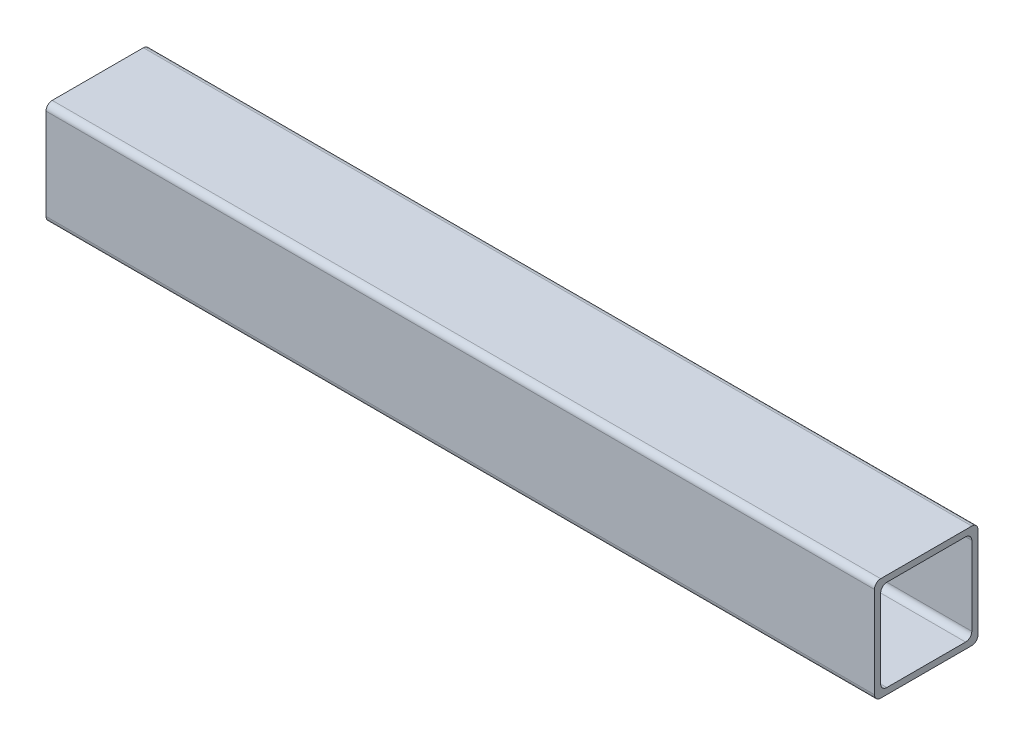
SolidWorks part; units mm, degrees
ref_plane "Front Plane" through (0, 0, 0) normal (0, 0, 1) x (1, 0, 0)
ref_plane "Top Plane" through (0, 0, 0) normal (0, 1, 0) x (1, 0, 0)
ref_plane "Right Plane" through (0, 0, 0) normal (1, 0, 0) x (0, 0, -1)
sketch "Sketch1" plane through (0, 0, 0) normal (1, 0, 0) x (0, 0, -1)
  line L1 (1.5, 0) -> (23.5, 0)
  line L2 (0, 1.5) -> (0, 23.5)
  line L3 (1.5, 25) -> (23.5, 25)
  line L4 (25, 1.5) -> (25, 23.5)
  line L5 (3, 23.5) -> (22, 23.5)
  line L6 (1.5, 22) -> (1.5, 3)
  line L7 (3, 1.5) -> (22, 1.5)
  line L8 (23.5, 22) -> (23.5, 3)
  arc A0 (23.5, 25) -> (25, 23.5) centre (23.5, 23.5) cw
  arc A1 (22, 23.5) -> (23.5, 22) centre (22, 22) cw
  arc A2 (23.5, 0) -> (25, 1.5) centre (23.5, 1.5) ccw
  arc A3 (22, 1.5) -> (23.5, 3) centre (22, 3) ccw
  arc A4 (1.5, 3) -> (3, 1.5) centre (3, 3) ccw
  arc A5 (1.5, 0) -> (0, 1.5) centre (1.5, 1.5) cw
  arc A6 (1.5, 22) -> (3, 23.5) centre (3, 22) cw
  arc A7 (0, 23.5) -> (1.5, 25) centre (1.5, 23.5) cw
  point P13 (23.5, 23.5)
  point P16 (25, 0)
  point P21 (1.5, 1.5)
  point P24 (0, 0)
  point P27 (1.5, 23.5)
  point P30 (0, 25)
  dimension "D6" = 1.5
  dimension "D1" = 25
  dimension "D2" = 25
  dimension "D3" = 22
  dimension "22" = 22
  dimension "D4" = 1.5
  dimension "D5" = 1.5
extrude "Boss-Extrude1" add sketch "Sketch1" along normal blind 200
